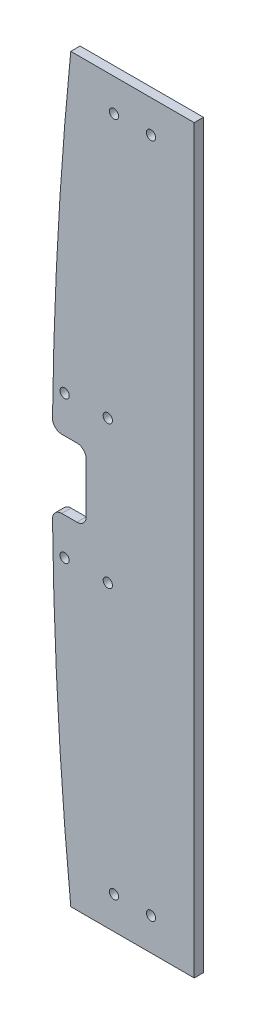
SolidWorks part; units mm, degrees
ref_plane "前视基准面" through (0, 0, 0) normal (0, 0, 1) x (1, 0, 0)
ref_plane "上视基准面" through (0, 0, 0) normal (0, 1, 0) x (1, 0, 0)
ref_plane "右视基准面" through (0, 0, 0) normal (1, 0, 0) x (0, 0, -1)
sketch "Model" plane through (0, 0, 0) normal (0, 0, 1) x (1, 0, 0)
  line L0 (2493.3663, 1849.3912) -> (2493.3663, 1609.3912)
  line L1 (2453.3663, 1849.3912) -> (2493.3663, 1849.3912)
  line L2 (2453.3663, 1609.3912) -> (2493.3663, 1609.3912)
  line L3 (2455.3663, 1718.2912) -> (2450.4492, 1718.2912)
  line L4 (2455.3663, 1740.4912) -> (2450.4492, 1740.4912)
  line L5 (2458.3663, 1721.2912) -> (2458.3663, 1737.4912)
  arc A0 (2453.3663, 1849.3912) -> (2447.4494, 1743.5265) centre (3650.3663, 1729.3912) ccw
  arc A1 (2447.4494, 1743.5265) -> (2450.4492, 1740.4912) centre (2450.4492, 1743.4912) ccw
  arc A2 (2447.4494, 1715.256) -> (2453.3663, 1609.3912) centre (3650.3663, 1729.3912) ccw
  arc A3 (2450.4492, 1718.2912) -> (2447.4494, 1715.256) centre (2450.4492, 1715.2912) ccw
  arc A4 (2455.3663, 1718.2912) -> (2458.3663, 1721.2912) centre (2455.3663, 1721.2912) ccw
  arc A5 (2458.3663, 1737.4912) -> (2455.3663, 1740.4912) centre (2455.3663, 1737.4912) ccw
  circle A6 centre (2479.3663, 1619.8912) radius 1.5
  circle A7 centre (2467.3663, 1619.8912) radius 1.5
  circle A8 centre (2467.3663, 1838.8912) radius 1.5
  circle A9 centre (2479.3663, 1838.8912) radius 1.5
  circle A10 centre (2465.3663, 1752.4912) radius 1.5
  circle A11 centre (2465.3663, 1706.2912) radius 1.5
  circle A12 centre (2451.3663, 1706.2912) radius 1.5
  circle A13 centre (2451.3663, 1752.4912) radius 1.5
extrude "凸台-拉伸1" add sketch "Model" along normal blind 3
